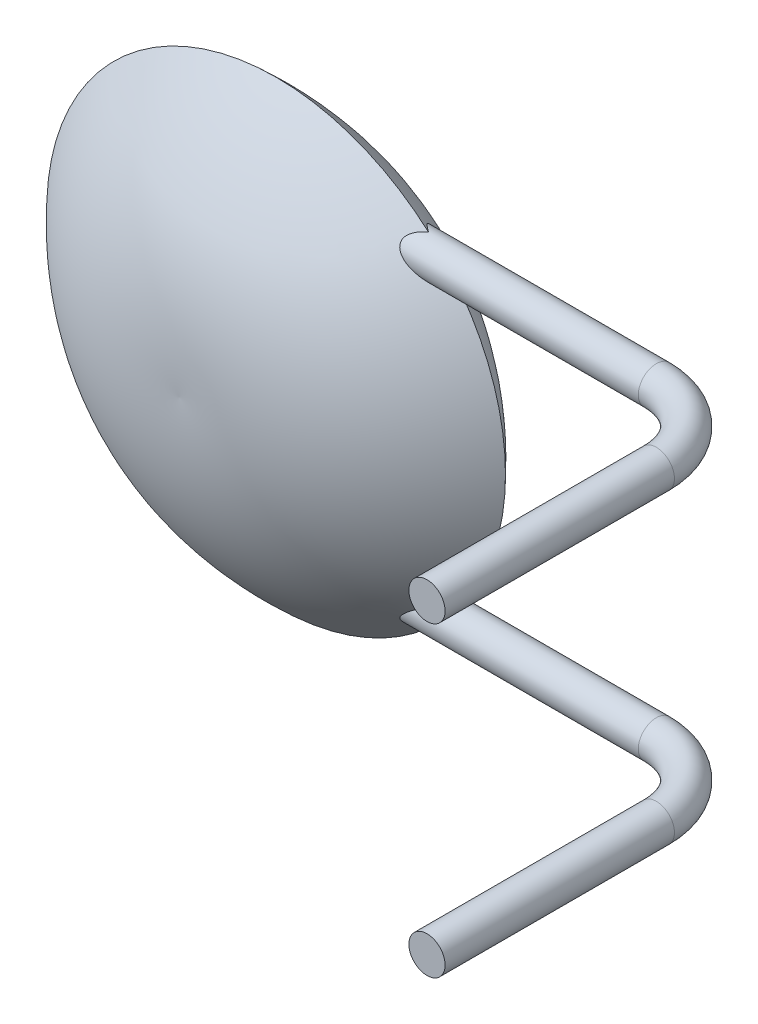
SolidWorks part; units mm, degrees
ref_plane "Front Plane" through (0, 0, 0) normal (0, 0, 1) x (1, 0, 0)
ref_plane "Top Plane" through (0, 0, 0) normal (0, 1, 0) x (1, 0, 0)
ref_plane "Right Plane" through (0, 0, 0) normal (1, 0, 0) x (0, 0, -1)
sketch "Sketch3" plane through (0, 0, 0) normal (0, 1, 0) x (1, 0, 0)
  line L0 (0, 0) -> (1.9, 0)
  line L1 (0, -0.8) -> (0, 0.8)
  line L2 (-55, 0) -> (55, 0) construction
  spline S0 degree 2 poles (0, 0.8) (1.1069, 0.865) (1.9, 0) knots 0 0 0 1 1 1
  spline S1 degree 2 poles (0, -0.8) (1.1069, -0.865) (1.9, 0) knots 0 0 0 1 1 1
  dimension "D1" = 1.9
  dimension "D2" = 0.8
revolve "Revolve1" add sketch "Sketch3" angle 360 about L1
sketch "Sketch4" plane through (0, 0, 0) normal (1, 0, 0) x (0, 0, -1)
  line L0 (0, 1.9) -> (0, -1.9) construction
  circle A0 centre (0, 1.27) radius 0.15
  dimension "D1" = 0.3
  dimension "D2" = 1.27
ref_plane "Plane1" through (0, 1.27, 0) normal (0, 1, 0) x (1, 0, 0)
sketch "Sketch5" plane through (0, 1.27, 0) normal (0, 1, 0) x (1, 0, 0)
  line L0 (0, 0) -> (3.15, 0)
  line L1 (3.75, -0.6) -> (3.75, -2.5)
  arc A0 (3.75, -0.6) -> (3.15, 0) centre (3.15, -0.6) ccw
  point P6 (3.75, 0)
  dimension "D3" = 0.6
  dimension "D1" = 3.75
  dimension "D2" = 2.5
sweep "Sweep1" add profiles "Sketch4" path "Sketch5"
mirror "Mirror1" about plane through (0, 0, 0) normal (0, 1, 0) of "Sweep1"
